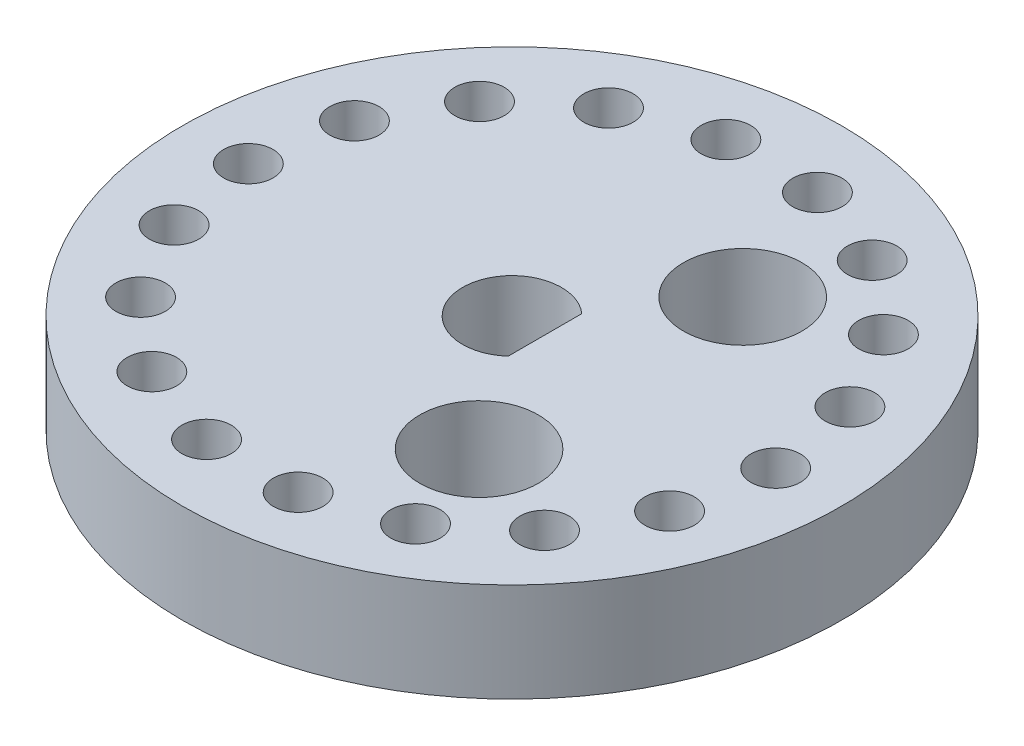
SolidWorks part; units mm, degrees
ref_plane "前视基准面" through (0, 0, 0) normal (0, 0, 1) x (1, 0, 0)
ref_plane "上视基准面" through (0, 0, 0) normal (0, 1, 0) x (1, 0, 0)
ref_plane "右视基准面" through (0, 0, 0) normal (1, 0, 0) x (0, 0, -1)
sketch "草图1" plane through (0, 0, 0) normal (0, 1, 0) x (1, 0, 0)
  circle A0 centre (0, 0) radius 10
extrude "凸台-拉伸1" add sketch "草图1" along normal blind 3
sketch "草图2" plane through (0, 3, 0) normal (0, 1, 0) x (1, 0, 0)
  line L9 (1, 1.118) -> (1, -1.118)
  arc A5 (1, 1.118) -> (1, -1.118) centre (0, 0) ccw
  point P7 (0, 0)
  point P30 (0, 0)
sketch "草图3" plane through (0, 3, 0) normal (0, 1, 0) x (1, 0, 0)
  circle A19 centre (0, 0) radius 8 construction
  circle A38 centre (8, 0) radius 0.75
  circle A39 centre (7.5175, -2.7362) radius 0.75
  circle A40 centre (6.1284, -5.1423) radius 0.75
  circle A41 centre (4, -6.9282) radius 0.75
  circle A42 centre (1.3892, -7.8785) radius 0.75
  circle A43 centre (-1.3892, -7.8785) radius 0.75
  circle A44 centre (-4, -6.9282) radius 0.75
  circle A45 centre (-6.1284, -5.1423) radius 0.75
  circle A46 centre (-7.5175, -2.7362) radius 0.75
  circle A47 centre (-8, 0) radius 0.75
  circle A48 centre (-7.5175, 2.7362) radius 0.75
  circle A49 centre (-6.1284, 5.1423) radius 0.75
  circle A50 centre (-4, 6.9282) radius 0.75
  circle A51 centre (-1.3892, 7.8785) radius 0.75
  circle A52 centre (1.3892, 7.8785) radius 0.75
  circle A53 centre (4, 6.9282) radius 0.75
  circle A54 centre (6.1284, 5.1423) radius 0.75
  circle A55 centre (7.5175, 2.7362) radius 0.75
  point P41 (0, 0)
  point P42 (0, 0)
  point P79 (0, 0)
  dimension "D1" = 18
extrude "切除-拉伸2" cut sketch "草图3" against normal through all
sketch "草图4" plane through (0, 3, 0) normal (0, 1, 0) x (1, 0, 0)
  line L2 (-10, 0) -> (10, 0) construction
  line L3 (0, 0) -> (3, 0) construction
  line L4 (3, 0) -> (3, -4) construction
  circle A3 centre (3, -4) radius 1.8
  circle A4 centre (3, 4) radius 1.8
extrude "切除-拉伸3" cut sketch "草图4" against normal through all
extrude "切除-拉伸6" cut sketch "草图2" against normal up to next
